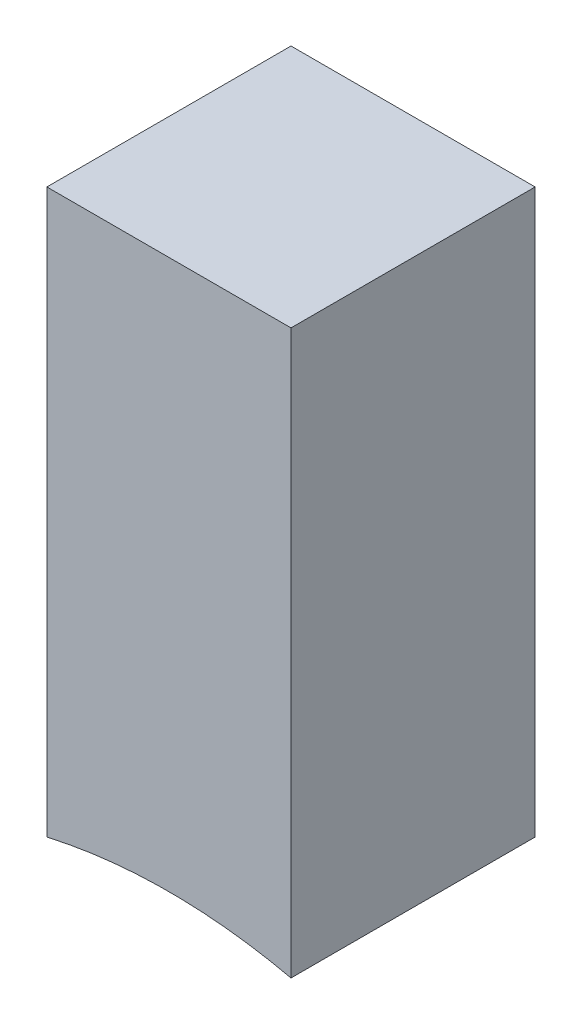
SolidWorks part; units mm, degrees
material "C (Graphit)"
ref_plane "Vorne" through (0, 0, 0) normal (0, 0, 1) x (1, 0, 0)
ref_plane "Oben" through (0, 0, 0) normal (0, 1, 0) x (1, 0, 0)
ref_plane "Rechts" through (0, 0, 0) normal (1, 0, 0) x (0, 0, -1)
sketch "Skizze1" plane through (0, 0, 0) normal (0, 0, 1) x (1, 0, 0)
  line L1 (-2, 5) -> (2, 5)
  line L2 (-2, 5) -> (-2, -5)
  line L3 (-2, -5) -> (2, -5)
  line L4 (2, 5) -> (2, -5)
  line L5 (-2, 5) -> (2, -5) construction
  line L6 (-2, -5) -> (2, 5) construction
  point P0 (0, 0)
  dimension "D1" = 4
  dimension "D2" = 10
extrude "Aufsatz-Linear austragen1" add sketch "Skizze1" along normal blind 4
sketch "Skizze2" plane through (0, 0, 4) normal (0, 0, 1) x (1, 0, 0)
  line L2 (2, -5) -> (2, 5) construction
  line L4 (-2, -5) -> (2, -5) construction
  circle A0 centre (0, -13) radius 9
  point P6 (0.1138, -6.8121)
  dimension "D2" = 18
  dimension "D1" = 2
  dimension "D3" = 8
extrude "Schnitt-Linear austragen1" cut sketch "Skizze2" against normal blind 4
